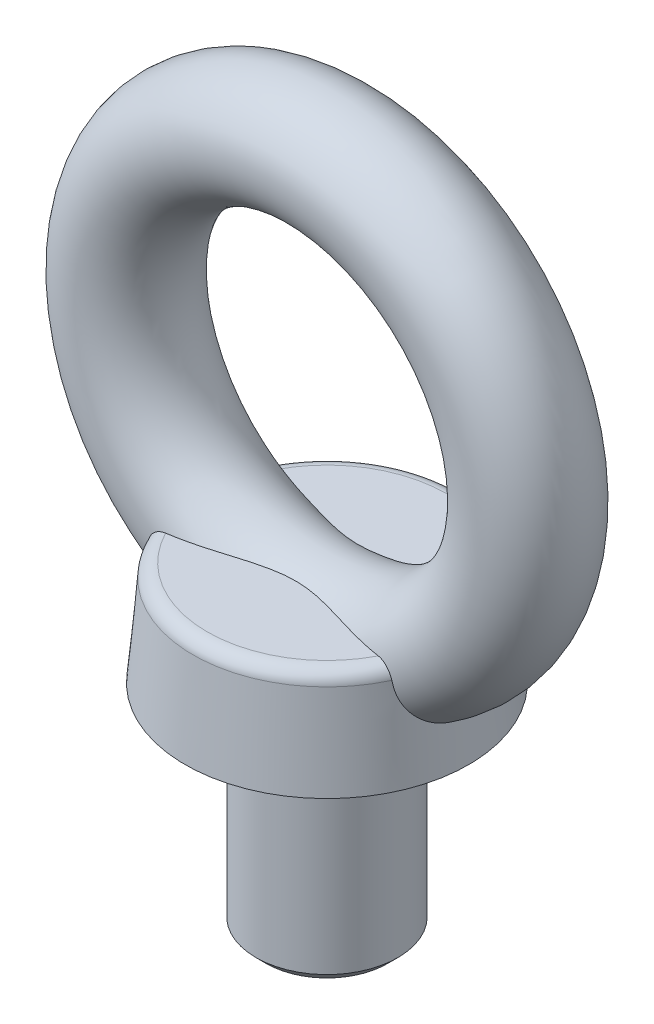
SolidWorks part; units mm, degrees
ref_plane "Płaszczyzna przednia" through (0, 0, 0) normal (0, 0, 1) x (1, 0, 0)
ref_plane "Płaszczyzna górna" through (0, 0, 0) normal (0, 1, 0) x (1, 0, 0)
ref_plane "Płaszczyzna prawa" through (0, 0, 0) normal (1, 0, 0) x (0, 0, -1)
sketch "Szkic1" plane through (0, 0, 0) normal (1, 0, 0) x (0, 0, -1)
  line L0 (12, 54.5) -> (-12, 54.5) construction
  circle A0 centre (0, 97) radius 12
sketch "Szkic2" plane through (0, 0, 0) normal (0, 0, 1) x (1, 0, 0)
  line L0 (0, 22) -> (25.3263, 22)
  line L1 (28.3148, 19.2615) -> (30, 0)
  line L2 (30, 0) -> (0, 0)
  line L3 (0, 0) -> (0, 22)
  line L4 (0, 0) -> (0, 22) construction
  arc A0 (25.3263, 22) -> (28.3148, 19.2615) centre (25.3263, 19) cw
revolve "Obrót1" add sketch "Szkic2" angle 360 about L4
revolve "Obrót2" add sketch "Szkic1" angle 360 about L0
sketch "Szkic3" plane through (0, 0, 0) normal (0, 0, 1) x (1, 0, 0)
  line L0 (0, 0) -> (15, 0)
  line L1 (15, 0) -> (15, -42.853)
  line L2 (15, -42.853) -> (12.853, -45)
  line L3 (12.853, -45) -> (0, -45)
  line L4 (0, -45) -> (0, 0)
  line L5 (0, -45) -> (0, 0) construction
revolve "Obrót3" add sketch "Szkic3" angle 360 about L5
cosmetic thread "Oznaczenie gwintu1" parameters "D1"=39, "D2"=25.706
sketch "Szkic4" plane through (0, 0, 0) normal (0, 0, 1) x (1, 0, 0)
  line L0 (13.5, 0) -> (13.5, -4.5)
  line L1 (13.5, -4.5) -> (15, -6)
  line L2 (15, -6) -> (15, 0)
  line L3 (15, 0) -> (13.5, 0)
  line L4 (0, -45) -> (0, 0) construction
revolve "Wycięcie-obrót1" cut sketch "Szkic4" angle 360 about L4
